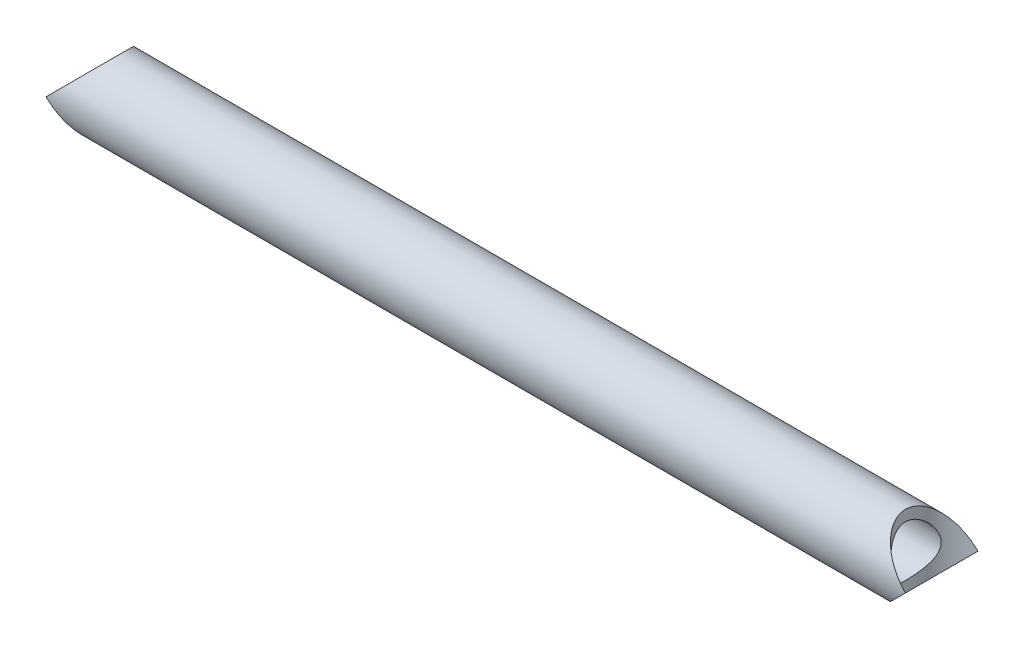
SolidWorks part; units mm, degrees
ref_plane "Front Plane" through (0, 0, 0) normal (0, 0, 1) x (1, 0, 0)
ref_plane "Top Plane" through (0, 0, 0) normal (0, 1, 0) x (1, 0, 0)
ref_plane "Right Plane" through (0, 0, 0) normal (1, 0, 0) x (0, 0, -1)
sketch "Sketch1" plane through (0, 0, 0) normal (0, 1, 0) x (1, 0, 0)
  line L0 (0, 0) -> (1184.76, 0)
  dimension "D1" = 1184.76
sketch "Sketch2" plane through (0, 0, 0) normal (1, 0, 0) x (0, 0, -1)
  circle A0 centre (0, 0) radius 50
  circle A1 centre (0, 0) radius 35
  dimension "D1" = 100
  dimension "D2" = 15
sweep "Sweep1" add profiles "Sketch2" path "Sketch1"
sketch "Sketch3" plane through (0, 0, 0) normal (0, 1, 0) x (1, 0, 0)
  line L0 (1184.76, -50) -> (1184.76, 50) construction
  circle A0 centre (0, 0) radius 50
  circle A1 centre (1184.76, 0) radius 50
  dimension "D1" = 100
  dimension "D2" = 100
extrude "Cut-Extrude1" cut sketch "Sketch3" against normal through all both and the other way through all
equation "\"hatchHoleDiameter\"= 600mm"
equation "\"hullThickness\"= 120mm"
equation "\"gasketHullInterconnectWidth\"= 100mm"
equation "\"collarThickness\"= 15"
equation "\"hatchTunnelLength\"=200"
equation "\"oRingDiameter\"=2"
equation "\"boltPatternRadiusInterconnect\"=500"
equation "\"interconnectBoltDiameter\"=30"
equation "\"hatchShaftDiameter\"=20"
equation "\"hatchMinima\"=50"
equation "\"hullDiameter\"=2000"
equation "\"hatchMaxima\"=180"
equation "\"bushingFlatHatch\"=15"
equation "\"hingePivotDiameter\"=20"
equation "\"handleWidth\"=250"
equation "\"handleHeight\"=160"
equation "\"handleThickness\"=25"
equation "\"FrameLength\"= 4300"
equation "\"FrameMidLength\"= 3000"
equation "\"TubeOD\"= 100"
equation "\"FrameBackFlat\"= 800"
equation "\"TubeWall\"=15"
equation "\"TopMemberAngle\"=120"
equation "\"FrameHight\"= 2500"
equation "\"D1@Sketch2\"=\"TubeOD\""
equation "\"D2@Sketch2\"=\"TubeWall\""
equation "\"D1@Sketch3\"=\"TubeOD\""
equation "\"D2@Sketch3\"=\"TubeOD\""
